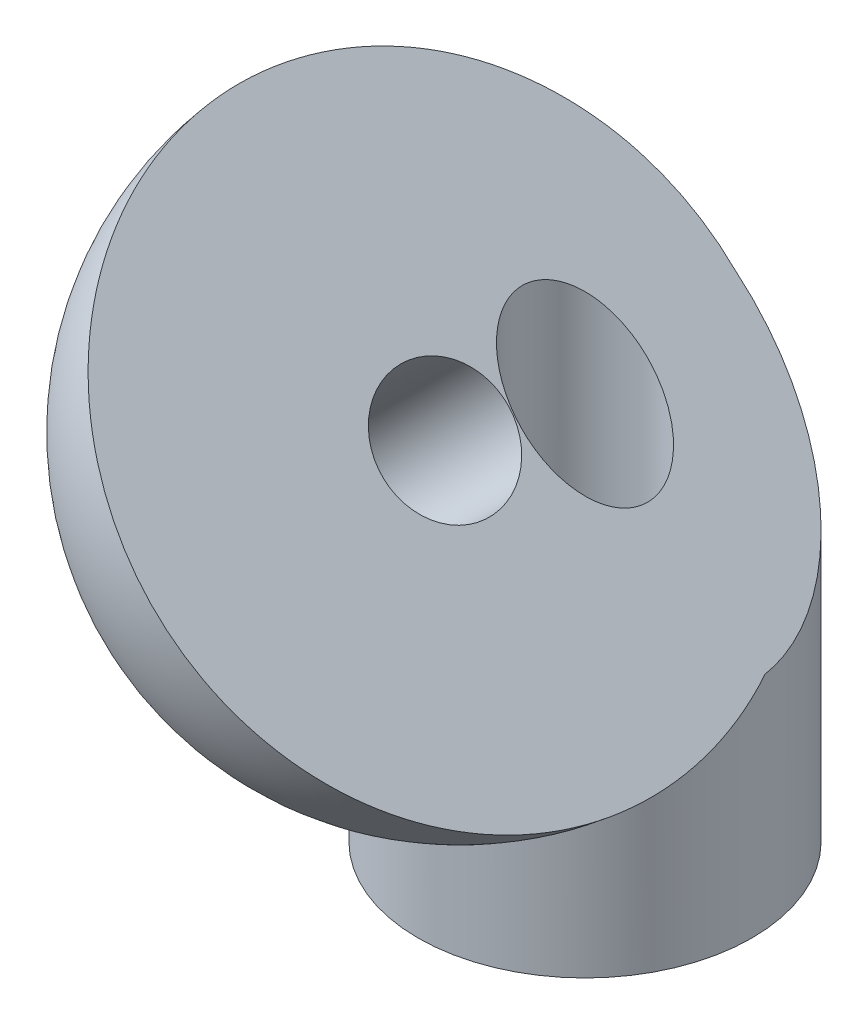
SolidWorks part; units mm, degrees
ref_plane "Front Plane" through (0, 0, 0) normal (0, 0, 1) x (1, 0, 0)
ref_plane "Top Plane" through (0, 0, 0) normal (0, 1, 0) x (1, 0, 0)
ref_plane "Right Plane" through (0, 0, 0) normal (1, 0, 0) x (0, 0, -1)
sketch "Sketch1" plane through (0, 0, 0) normal (0, 1, 0) x (1, 0, 0)
  circle A0 centre (0, 0) radius 4
  dimension "D2" = 8
extrude "Boss-Extrude1" add sketch "Sketch1" along normal blind 10
sketch "Sketch2" plane through (0, 0, 0) normal (1, 0, 0) x (0, 0, -1)
  line L0 (-3, 3) -> (-3, 17)
  arc A0 (-3, 17) -> (-3, 3) centre (-3, 10) cw
  dimension "D1" = 17
ref_axis "Axis2" through (0, 3, 3) along (0, 1, 0)
revolve "Revolve2" add sketch "Sketch2" angle 360 about axis through (0, 3, 3) along (0, 1, 0)
sketch "Sketch5" plane through (0, 0, 0) normal (0, 0, 1) x (1, 0, 0)
  line L0 (-7, 17) -> (7, 3) construction
  line L1 (-7, 13.9245) -> (-7, -49986.0755) construction
  line L2 (-8.6444, 3) -> (49991.3556, 3) construction
  line L3 (-7, 17) -> (7, 17)
  line L4 (7, 17) -> (7, 3)
  line L5 (-7, 17) -> (-7.3536, 16.6464)
  line L6 (-7.3536, 16.6464) -> (6.6464, 2.6464)
  line L7 (6.6464, 2.6464) -> (7, 3)
  circle A1 centre (0, 10) radius 7 construction
  dimension "D1" = 45
  dimension "D2" = 0.5
extrude "Cut-Extrude1" cut sketch "Sketch5" against normal through all and the other way through all
sketch "Sketch9" plane through (4.6464, 4.6464, 0) normal (0.7071, 0.7071, 0) x (0, 0, -1)
  circle A0 centre (-3, 7.0711) radius 1.5
  circle A1 centre (-3, 7.0711) radius 6.9821 construction
  dimension "D1" = 3
extrude "Cut-Extrude5" cut sketch "Sketch9" against normal through all
sketch "Sketch7" plane through (0, 0, 0) normal (0, -1, 0) x (1, 0, 0)
  circle A0 centre (0, 0) radius 1.5
  dimension "D1" = 3
extrude "Cut-Extrude3" cut sketch "Sketch7" against normal through all
